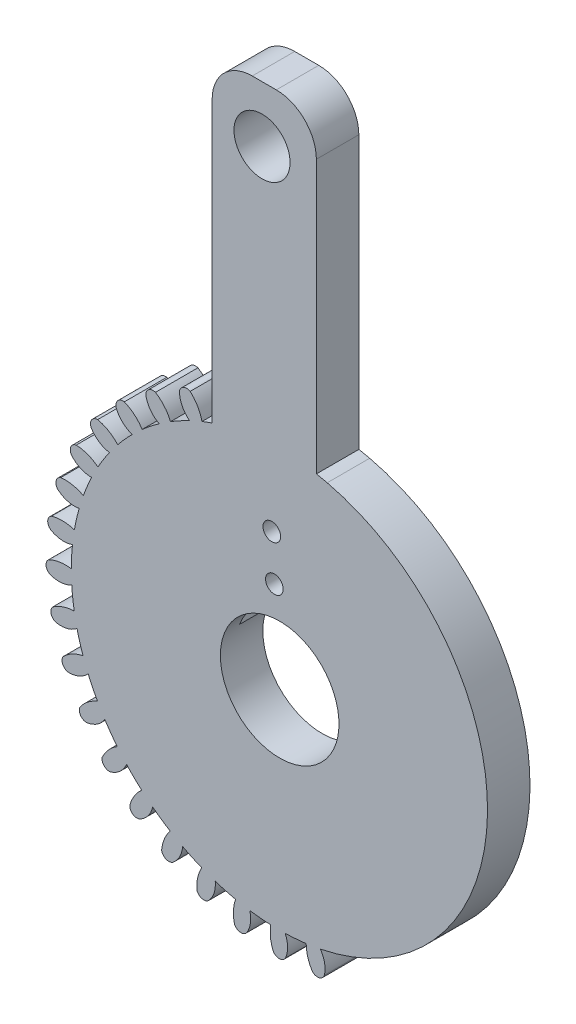
SolidWorks part; units mm, degrees
ref_plane "Front Plane" through (0, 0, 0) normal (0, 0, 1) x (1, 0, 0)
ref_plane "Top Plane" through (0, 0, 0) normal (0, 1, 0) x (1, 0, 0)
ref_plane "Right Plane" through (0, 0, 0) normal (1, 0, 0) x (0, 0, -1)
sketch "Sketch1" plane through (0, 0, 0) normal (0, 0, 1) x (1, 0, 0)
  circle A0 centre (0, 0) radius 13
extrude "Boss-Extrude1" add sketch "Sketch1" along normal blind 2.65
sketch "Sketch2" plane through (0, 0, 2.65) normal (0, 0, 1) x (1, 0, 0)
  line L0 (-1.4072, 12.9236) -> (-0.5647, 12.9877)
  arc A0 (-0.5647, 12.9877) -> (-0.8397, 14.4228) centre (-2.9593, 13.2728) ccw
  circle A1 centre (0, 0) radius 13 construction
  arc A2 (-0.8397, 14.4228) -> (-1.5928, 14.2987) centre (-1.1777, 14.1267) ccw
  arc A3 (-1.5928, 14.2987) -> (-1.4072, 12.9236) centre (-0.0609, 13.8053) ccw
extrude "Boss-Extrude2" add sketch "Sketch2" against normal blind 2.65
pattern_circular "CirPattern1" count 37 over 360 about axis through (-0.0032, 0.0389, 0) along (0, 0, 1) of "Boss-Extrude2"
sketch "Sketch3" plane through (0, 0, 2.65) normal (0, 0, 1) x (1, 0, 0)
  arc A0 (2.5398, -12.7495) -> (2.9649, 12.6574) centre (-0.0422, 0.0007) ccw
  arc A1 (3.036, -15.1997) -> (3.5428, 15.0897) centre (-0.0422, 0.0007) ccw
  arc A2 (2.5398, -12.7495) -> (3.036, -15.1997) centre (1.5628, -14.2227) cw
  arc A3 (3.5428, 15.0897) -> (2.9649, 12.6574) centre (4.47, 13.5846) ccw
  dimension "D1" = 2.5
extrude "Cut-Extrude1" cut sketch "Sketch3" against normal blind 6
sketch "Sketch5" plane through (0, 0, 2.65) normal (0, 0, 1) x (1, 0, 0)
  line L1 (-4.2117, 12.2988) -> (2.2883, 12.2988)
  line L2 (-4.2117, 12.2988) -> (-4.2117, 32.2988)
  line L3 (-4.2117, 32.2988) -> (2.2883, 32.2988)
  line L4 (2.2883, 12.2988) -> (2.2883, 32.2988)
  arc A0 (-3.5651, 12.5016) -> (-4.8468, 12.0627) centre (0, 0) ccw construction
  dimension "D1" = 20
  dimension "D2" = 6.5
extrude "Boss-Extrude3" add sketch "Sketch5" against normal blind 2.65
fillet "Fillet1" radius 2.5 2 edges at (2.2883, 32.2988, 1.325) (-4.2117, 32.2988, 1.325)
sketch "Sketch6" plane through (0, 0, 0) normal (0, 0, -1) x (-1, 0, 0)
  circle A0 centre (0, 0) radius 3.7
  dimension "D1" = 7.4
extrude "Cut-Extrude2" cut sketch "Sketch6" against normal through all contours A0
sketch "Sketch7" plane through (0, 0, 0) normal (0, 0, -1) x (-1, 0, 0)
  line L0 (3.4574, 1.3177) -> (2.9338, 10.4369)
  line L1 (-2.9157, 2.2779) -> (-1.1125, 11.4725)
  circle A1 centre (0, 0) radius 3.7 construction
  arc A4 (3.4574, 1.3177) -> (-2.9157, 2.2779) centre (0, 0) ccw
  arc A5 (-1.1125, 11.4725) -> (2.9338, 10.4369) centre (0.5783, 9.656) cw
sketch "Sketch8" plane through (0, 0, 0) normal (0, 0, -1) x (-1, 0, 0)
  line L0 (0.2117, 32.2988) -> (1.7117, 32.2988) construction
  circle A0 centre (1.1012, 28.7988) radius 1.75
  dimension "D1" = 3.5
  dimension "D2" = 3.5
extrude "Cut-Extrude4" cut sketch "Sketch8" against normal through all
extrude "Cut-Extrude5" cut sketch "Sketch7" against normal blind 1.7
sketch "Sketch9" plane through (0, 0, 1.7) normal (0, 0, -1) x (-1, 0, 0)
  circle A0 centre (0.3308, 5.5358) radius 0.55
  circle A1 centre (0.4908, 8.2944) radius 0.55
extrude "Cut-Extrude6" cut sketch "Sketch9" against normal through all
